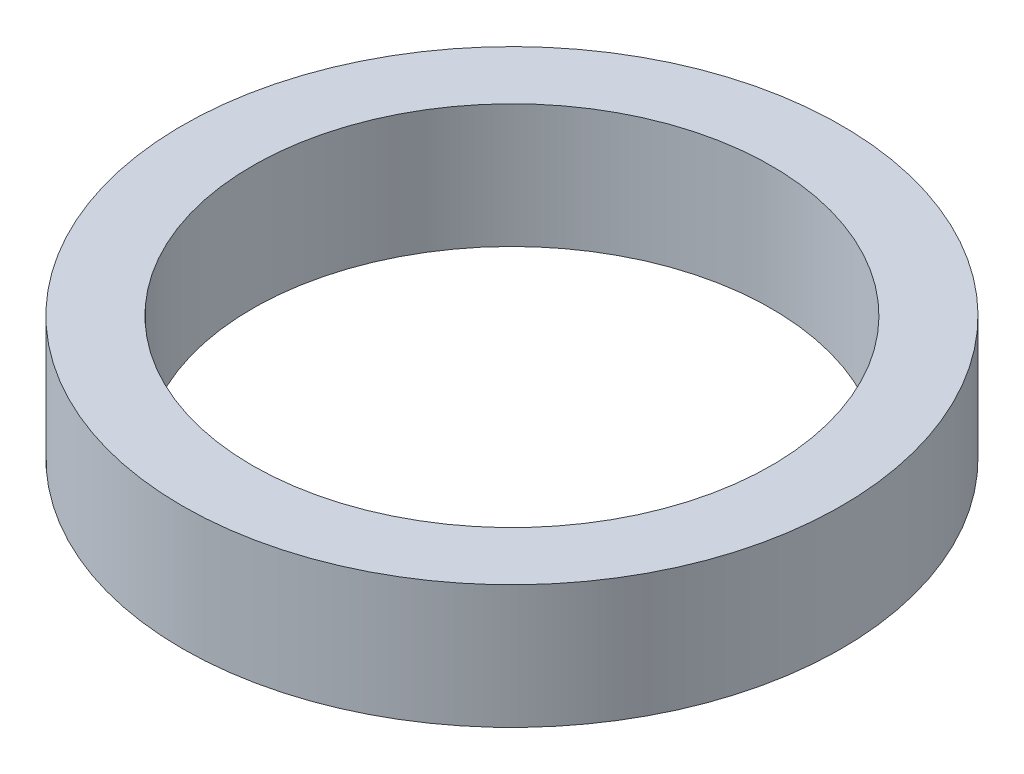
SolidWorks part; units mm, degrees
material "ABS"
ref_plane "Front Plane" through (0, 0, 0) normal (0, 0, 1) x (1, 0, 0)
ref_plane "Top Plane" through (0, 0, 0) normal (0, 1, 0) x (1, 0, 0)
ref_plane "Right Plane" through (0, 0, 0) normal (1, 0, 0) x (0, 0, -1)
other "Configuration Table"
sketch "Sketch1" plane through (0, 0, 0) normal (0, 1, 0) x (1, 0, 0)
  circle A0 centre (0, 0) radius 3.15
  circle A1 centre (0, 0) radius 4
  dimension "D1" = 6.3
  dimension "D2" = 8
extrude "Boss-Extrude1" add sketch "Sketch1" along normal blind 1.5
